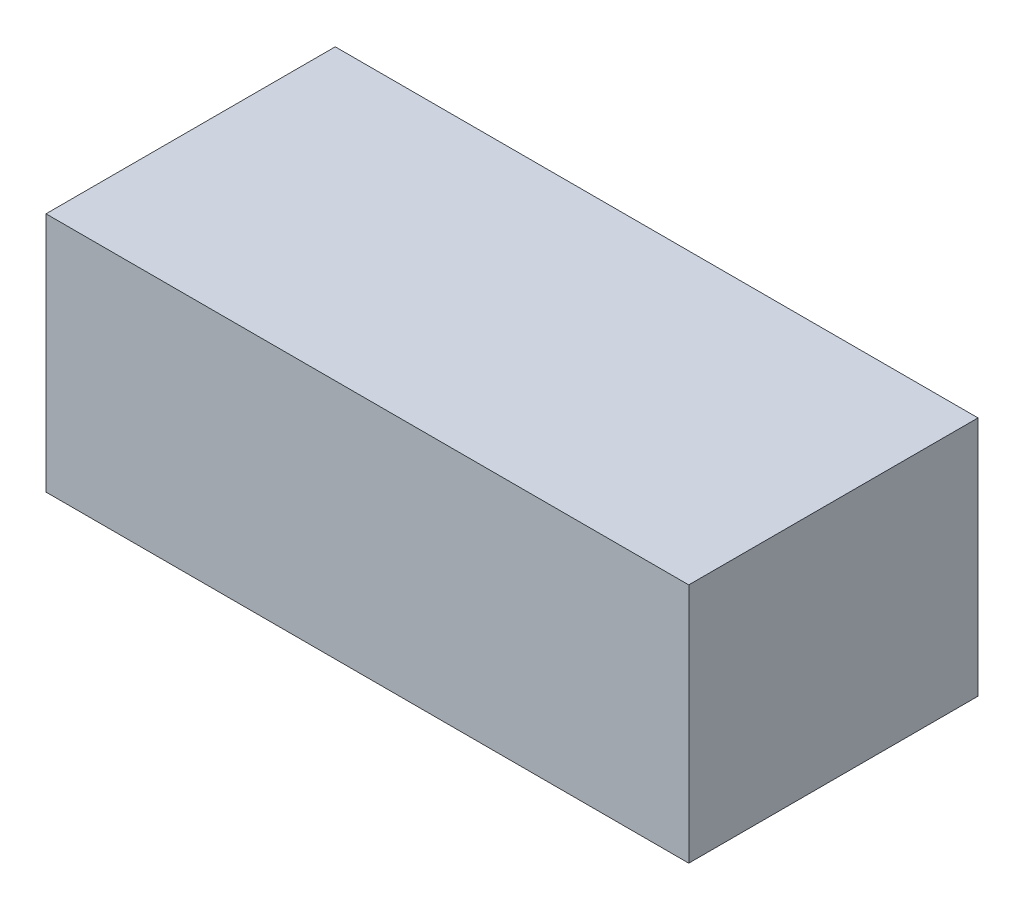
SolidWorks part; units mm, degrees
ref_plane "Front Plane" through (0, 0, 0) normal (0, 0, 1) x (1, 0, 0)
ref_plane "Top Plane" through (0, 0, 0) normal (0, 1, 0) x (1, 0, 0)
ref_plane "Right Plane" through (0, 0, 0) normal (1, 0, 0) x (0, 0, -1)
sketch "Sketch1" plane through (0, 0, 0) normal (0, 1, 0) x (1, 0, 0)
  line L1 (0, 0) -> (200, 0)
  line L2 (0, 0) -> (0, 90)
  line L3 (0, 90) -> (200, 90)
  line L4 (200, 0) -> (200, 90)
  dimension "D1" = 90
  dimension "D2" = 200
extrude "Boss-Extrude1" add sketch "Sketch1" along normal blind 75
